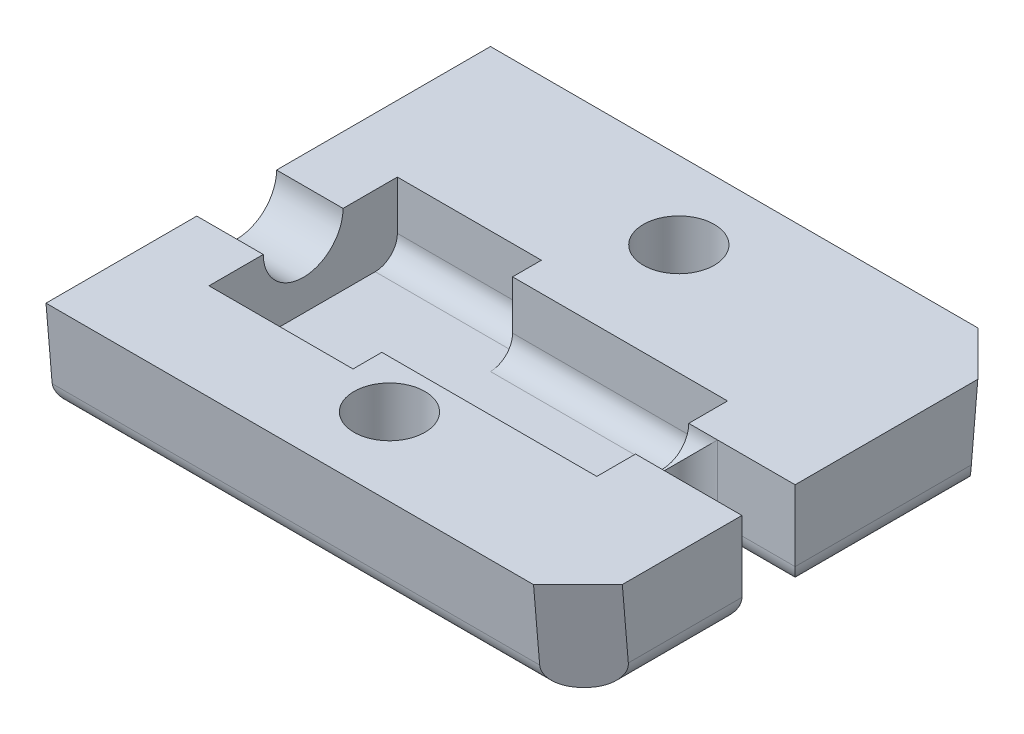
SolidWorks part; units mm, degrees
ref_plane "Front Plane" through (0, 0, 0) normal (0, 0, 1) x (1, 0, 0)
ref_plane "Top Plane" through (0, 0, 0) normal (0, 1, 0) x (1, 0, 0)
ref_plane "Right Plane" through (0, 0, 0) normal (1, 0, 0) x (0, 0, -1)
sketch "Sketch1" plane through (0, 0, 0) normal (0, 1, 0) x (1, 0, 0)
  line L0 (1, 1.8) -> (1, 8.25)
  line L1 (1, 8.25) -> (25, 8.25)
  line L2 (25, 8.25) -> (25, 2.95)
  line L3 (25, 2.95) -> (10.5, 2.95)
  line L4 (10.5, 2.95) -> (10.5, 4.25)
  line L5 (10.5, 4.25) -> (4, 4.25)
  line L6 (4, 4.25) -> (4, 1.8)
  line L7 (4, 1.8) -> (1, 1.8)
  line L8 (4.3388, 0) -> (-5.9836, 0) construction
  line L9 (25, 2.95) -> (25, 1.2)
  line L10 (25, 1.2) -> (20.2, 1.2)
  line L11 (20.2, 1.2) -> (20.2, 2.95)
  line L13 (25, -8.25) -> (25, -1.2) construction
  line L14 (10.5, 2.95) -> (10.5, 4.25) construction
  line L15 (4, -4.25) -> (4, 4.25) construction
  line L16 (1, 8.25) -> (1, -8.25) construction
  point P14 (20.2, 2.075)
  dimension "D1" = 3.6
  dimension "D2" = 5.3
  dimension "D5" = 5.9
  dimension "D6" = 8.5
  dimension "D8" = 2.4
  dimension "D9" = 4.8
extrude "Boss-Extrude1" add sketch "Sketch1" along normal blind 3.2 contours L11 L10 L9 L3
mirror "Mirror3" about plane through (0, 0, 0) normal (0, 0, 1) of bodies 101
sketch "Sketch2" plane through (0, 0, 0) normal (0, -1, 0) x (1, 0, 0)
  line L1 (1, 8.25) -> (25, 8.25)
  line L2 (1, 8.25) -> (1, -8.25)
  line L3 (1, -8.25) -> (25, -8.25)
  line L4 (25, 8.25) -> (25, -8.25)
extrude "Boss-Extrude2" add sketch "Sketch2" along normal blind 1
sketch "Sketch4" plane through (25, 0, 0) normal (1, 0, 0) x (0, 0, -1)
  line L0 (-1.2, 3.2) -> (-1.2, 0)
  line L1 (-1.2, 0) -> (1.2, 0)
  line L2 (1.2, 0) -> (1.2, 3.2)
  arc A0 (-1.2, 3.2) -> (1.2, 3.2) centre (0, 3.2) ccw
  dimension "D1" = 3.2
extrude "Boss-Extrude3" add sketch "Sketch4" against normal up to surface (4.8 mm away) up to face at (20.2, 1.6, -2.075)
sketch "Sketch5" plane through (1, 0, 0) normal (-1, 0, 0) x (0, 0, 1)
  line L0 (-1.8, 3.2) -> (-1.8, 0)
  line L1 (-1.8, 0) -> (1.8, 0)
  line L2 (1.8, 0) -> (1.8, 3.2)
  arc A0 (-1.8, 3.2) -> (1.8, 3.2) centre (0, 3.2) ccw
extrude "Boss-Extrude4" add sketch "Sketch5" against normal up to surface (3 mm away) up to face at (4, 1.6, 3.025)
sketch "Sketch6" plane through (0, -1, 0) normal (0, -1, 0) x (1, 0, 0)
  line L0 (25, -8.25) -> (25, 8.25) construction
  line L1 (21.5, 1.2) -> (25, 1.2)
  line L2 (21.5, -1.2) -> (25, -1.2)
  line L3 (25, -1.2) -> (25, 1.2)
  arc A0 (21.5, 1.2) -> (21.5, -1.2) centre (21.5, 0) ccw
  dimension "D1" = 3.5
  dimension "D2" = 2.4
extrude "Cut-Extrude1" cut sketch "Sketch6" against normal up to surface (4.2 mm away) up to face at (12.14, 3.2, 3.69)
sketch "Sketch8" plane through (25, 0, 0) normal (1, 0, 0) x (0, 0, -1)
  line L0 (-8.25, 3.2) -> (-8.6052, 3.2)
  line L1 (-8.6052, 3.2) -> (-8.25, -1)
  line L2 (-8.25, -1) -> (-8.25, 3.2)
  line L3 (8.25, 3.2) -> (8.25, -1)
  line L4 (8.25, -1) -> (11.07, -1)
  line L5 (11.07, -1) -> (11.4523, 3.2)
  line L6 (11.4523, 3.2) -> (8.25, 3.2)
  line L7 (-9.9835, 19.5) -> (-8.25, -1) construction
  line L8 (11.07, -1) -> (12.936, 19.5) construction
extrude "Boss-Extrude5" add sketch "Sketch8" against normal up to surface (24 mm away) up to face at (1, 1.5, 0)
sketch "Sketch7" plane through (0, 3.2, 0) normal (0, 1, 0) x (1, 0, 0)
  line L1 (25, 11.4523) -> (25, 1.2) construction
  line L2 (1.8966, 0) -> (19.8004, 0) construction
  line L3 (1, 11.4523) -> (25, 11.4523) construction
  line L4 (1, -8.6052) -> (25, -8.6052) construction
  circle A0 centre (13, 7.9523) radius 1.55
  circle A1 centre (13, -5.1052) radius 1.55
  dimension "D1" = 3.1
  dimension "D2" = 3.5
  dimension "D3" = 12
  dimension "D4" = 3.5
extrude "Cut-Extrude2" cut sketch "Sketch7" against normal blind 10
chamfer "Chamfer1" distance 2 angle 45 2 edges at (25, 1.1, 8.4276) (25, 1.1, -11.2612)
fillet "Fillet1" radius 1 8 edges at (23.25, -1, 1.2) (23.25, -1, -1.2) (25, -1, 3.7214) (12, -1, 8.25) (1, -1, -1.41) (12, -1, -11.07) (25, -1, -5.1309) (20.3, -1, 0)
hole_wizard "CSK for M3 Flat Head Machine Screw1" positions "Sketch9" profile "Sketch10" countersink size "M3" standard "ANSI Metric" end condition through all
sketch "Sketch9" plane through (0, -1, 0) normal (0, -1, 0) x (-1, 0, 0)
  point P0 (-13, -5.1052)
  point P3 (-13, 7.9523)
sketch "Sketch10" plane through (13, -1, 5.1052) normal (1, 0, 0) x (0, 0, -1)
  line L0 (0, 0) -> (0, 4.2)
  line L1 (0, 4.2) -> (1.6, 4.2)
  line L2 (1.6, 4.2) -> (1.6, 1.55)
  line L3 (1.6, 1.55) -> (3.15, 0)
  line L5 (3.15, 0) -> (0, 0)
  line L6 (-1.6, 1.55) -> (-3.15, 0) construction
  line L11 (0, -6.35) -> (0, 107.95) construction
  dimension "Thru Hole Dia." = 3.2
  dimension "Thru Hole Depth" = 4.2
  dimension "Near C'Sink Dia." = 6.3
  dimension "Near C'Sink Angle" = 90
fillet "Fillet2" radius 1 4 edges at (7.25, 0, -4.25) (15.35, 0, -2.95) (7.25, 0, 4.25) (15.35, 0, 2.95)
equation "\"extrude height\"= 3.2"
equation "\"D1@Boss-Extrude1\"=\"extrude height\""
equation "\"D1@Sketch4\"=\"extrude height\""
